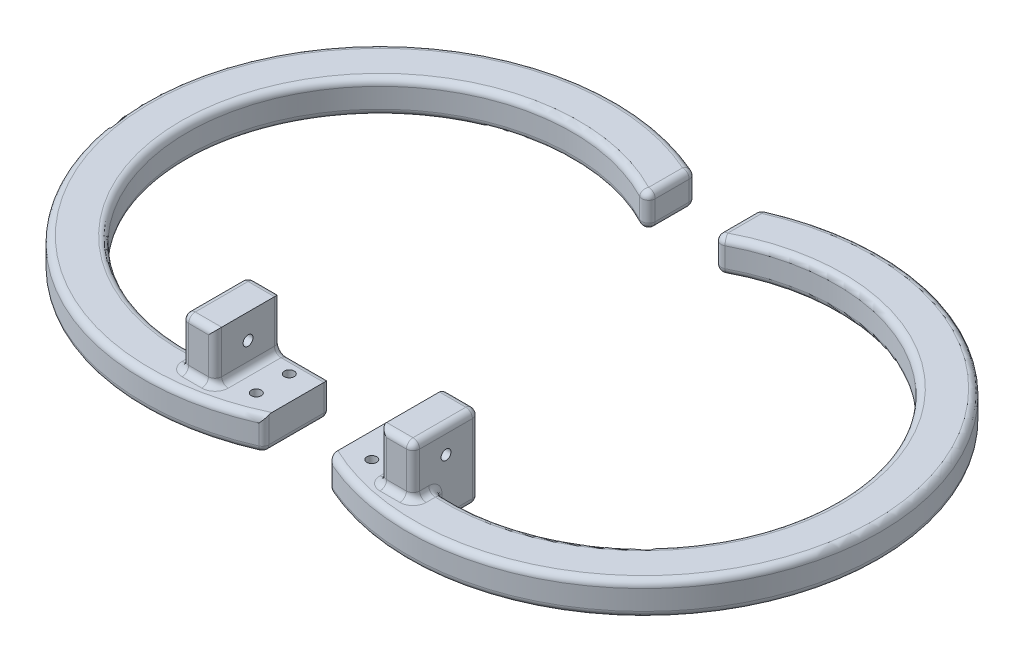
SolidWorks part; units mm, degrees
ref_plane "Front Plane" through (0, 0, 0) normal (0, 0, 1) x (1, 0, 0)
ref_plane "Top Plane" through (0, 0, 0) normal (0, 1, 0) x (1, 0, 0)
ref_plane "Right Plane" through (0, 0, 0) normal (1, 0, 0) x (0, 0, -1)
sketch "Sketch1" plane through (0, 0, 0) normal (0, 1, 0) x (1, 0, 0)
  line L0 (0, 0) -> (-20, 0) construction
  line L1 (-20, 0) -> (-20, 50) construction
  line L2 (-20, 0) -> (-20, -50) construction
  line L3 (-20, 50) -> (-20, 65)
  line L4 (-20, -50) -> (-20, -65)
  arc A0 (-20, 50) -> (-20, -50) centre (10, 0) cw
  arc A1 (-20, 65) -> (-20, -65) centre (10, 0) cw
  dimension "D5" = 0
  dimension "D1" = 30
  dimension "D2" = 50
  dimension "D3" = 15
  dimension "D4" = 15
extrude "Boss-Extrude1" add sketch "Sketch1" against normal blind 10
sketch "Sketch2" plane through (-20, 0, 0) normal (-1, 0, 0) x (0, 0, 1)
  line L1 (65, -10) -> (45, -10)
  line L2 (65, -10) -> (65, 0)
  line L3 (65, 0) -> (45, 0)
  line L4 (45, -10) -> (45, 0)
  dimension "D1" = 20
extrude "Boss-Extrude2" add sketch "Sketch2" against normal blind 15
sketch "Sketch3" plane through (-5, 0, 0) normal (1, 0, 0) x (0, 0, -1)
  line L3 (-45, 0) -> (-65, 0)
  line L4 (-45, 0) -> (-45, 15)
  line L5 (-45, 15) -> (-65, 15)
  line L6 (-65, 0) -> (-65, 15)
  dimension "D1" = 15
  dimension "D2" = 20
extrude "Boss-Extrude10" add sketch "Sketch3" along normal blind 10 separate body
sketch "Sketch4" plane through (0, 0, 0) normal (0, -1, 0) x (-1, 0, 0)
  line L1 (5, -45) -> (-5, -45)
  line L2 (5, -45) -> (5, -65)
  line L3 (5, -65) -> (-5, -65)
  line L4 (-5, -45) -> (-5, -65)
extrude "Boss-Extrude11" add sketch "Sketch4" along normal blind 10
fillet "Fillet2" radius 2 24 edges at (81.5891, -10, 0) (-20, -10, -57.5) (-7.5, -10, 45) (-20, -5, 45) (5, -5, 58.0948) (5, 2.5, 45) (66.8099, -10, -13.1389) (5, -10, 51.5474) (81.5891, 0, 0) (-12.5, 0, 45) (-5, 7.5, 45) (0, 15, 45) (-5, 7.5, 65) (0, 15, 65) (-5, 0, 55) (0, 0, 65) (5, 15, 55) (5, 7.5, 65) (5, 0, 61.5474) (66.8099, 0, -13.1389) (-20, -10, 55) (-20, -5, -50) (-20, -5, -65) (-20, -5, 65)
ref_plane "Plane1" through (0, 15, 0) normal (0, 1, 0) x (1, 0, 0)
sketch "Sketch5" plane through (0, 15, 0) normal (0, 1, 0) x (1, 0, 0)
  line L0 (-5, -55) -> (-12.5, -55) construction
  line L1 (-5, -47) -> (-5, -63) construction
  line L2 (-12.5, -55) -> (-12.5, -50) construction
  line L3 (-12.5, -55) -> (-12.5, -60) construction
  circle A0 centre (-12.5, -50) radius 1.5
  circle A1 centre (-12.5, -60) radius 1.5
  dimension "D1" = 7.5
  dimension "D2" = 5
  dimension "D3" = 5
extrude "Cut-Extrude1" cut sketch "Sketch5" against normal through all
ref_plane "Plane2" through (-5, 0, 0) normal (-1, 0, 0) x (0, 0, 1)
sketch "Sketch6" plane through (-5, 0, 0) normal (-1, 0, 0) x (0, 0, 1)
  line L0 (55, 15) -> (55, 8.7872) construction
  line L1 (47, 15) -> (63, 15) construction
  line L2 (63, 0) -> (47, 0) construction
  circle A0 centre (55, 7.5) radius 1.5
  dimension "D1" = 3
  dimension "D2" = 7.5
extrude "Cut-Extrude2" cut sketch "Sketch6" against normal up to next
ref_plane "Plane3" through (-30, 0, 0) normal (-1, 0, 0) x (0, 0, 1)
mirror "Mirror2" about plane through (-30, 0, 0) normal (-1, 0, 0) of bodies 106
